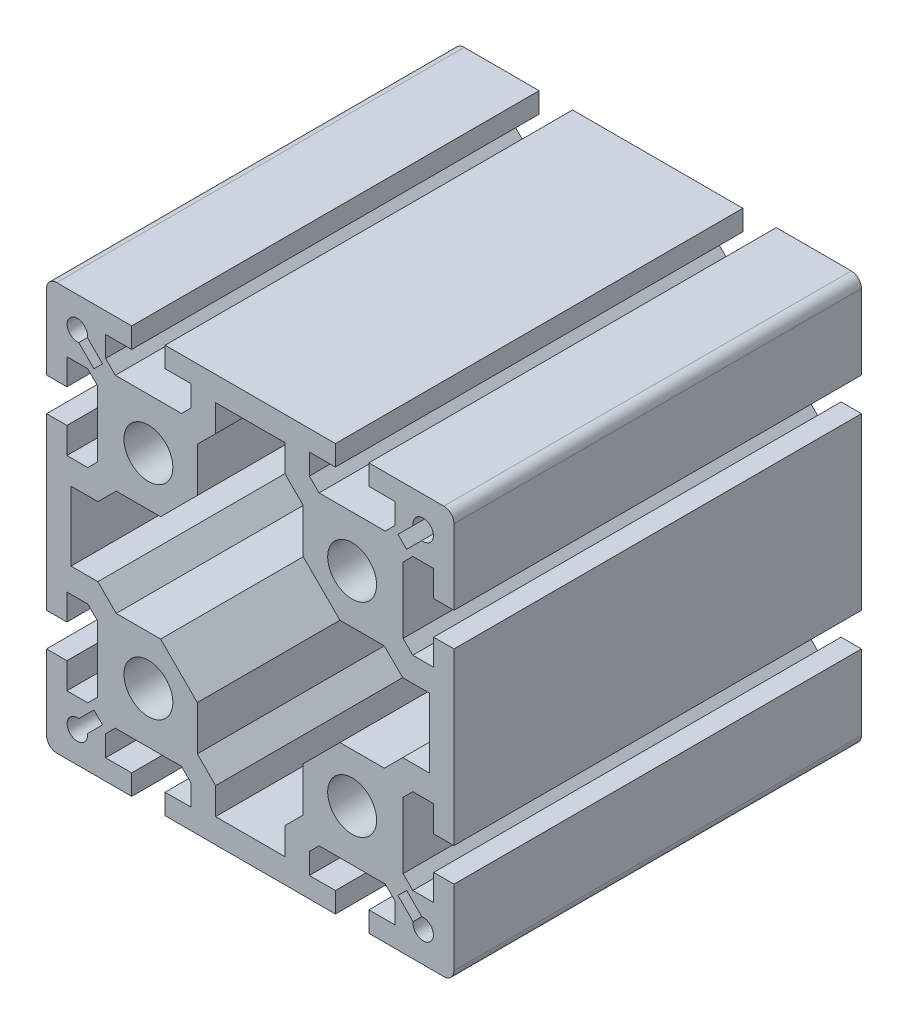
SolidWorks part; units mm, degrees
ref_plane "前视基准面" through (0, 0, 0) normal (0, 0, 1) x (1, 0, 0)
ref_plane "上视基准面" through (0, 0, 0) normal (0, 1, 0) x (1, 0, 0)
ref_plane "右视基准面" through (0, 0, 0) normal (1, 0, 0) x (0, 0, -1)
sketch "草图1" plane through (0, 0, 0) normal (0, 0, 1) x (1, 0, 0)
  line L0 (-28.6744, 51.3626) -> (-47.0744, 51.3626)
  line L1 (-49.5744, 48.8626) -> (-49.5744, 30.4626)
  line L2 (-24.5744, 38.8626) -> (-32.6903, 38.8626)
  line L3 (-37.0744, 34.4786) -> (-37.0744, 26.3626)
  line L4 (-28.6744, 46.3626) -> (-35.0744, 46.3626)
  line L5 (-44.5744, 36.8626) -> (-44.5744, 30.4626)
  line L6 (-35.0744, 46.3626) -> (-35.0744, 41.2467)
  line L7 (-28.6744, 51.3626) -> (-28.6744, 46.3626)
  line L8 (-39.4585, 36.8626) -> (-44.5744, 36.8626)
  line L9 (-44.5744, 30.4626) -> (-49.5744, 30.4626)
  line L10 (-32.6903, 38.8626) -> (-35.0744, 41.2467)
  line L11 (-37.0744, 34.4786) -> (-39.4585, 36.8626)
  line L12 (-35.8264, 39.7359) -> (-39.5416, 43.4511)
  line L13 (-37.9477, 37.6146) -> (-41.6629, 41.3298)
  line L14 (-37.9477, 37.6146) -> (-35.8264, 39.7359)
  line L15 (-24.5744, 38.8626) -> (-16.4585, 38.8626)
  line L16 (-20.4744, 46.3626) -> (-14.0744, 46.3626)
  line L17 (-14.0744, 46.3626) -> (-14.0744, 41.2467)
  line L18 (-8.0744, 45.3626) -> (-8.0744, 38.7614)
  line L19 (-20.4744, 51.3626) -> (-20.4744, 46.3626)
  line L20 (-16.4585, 38.8626) -> (-14.0744, 41.2467)
  line L21 (-12.5744, 34.2614) -> (-8.0744, 38.7614)
  line L22 (-20.4744, 51.3626) -> (0.4256, 51.3626)
  line L23 (-8.0744, 45.3626) -> (0.4256, 45.3626)
  line L24 (-37.0744, 26.3626) -> (-37.0744, 18.2467)
  line L25 (-44.5744, 22.2626) -> (-44.5744, 15.8626)
  line L26 (-44.5744, 15.8626) -> (-39.4585, 15.8626)
  line L27 (-37.0744, 18.2467) -> (-39.4585, 15.8626)
  line L28 (-49.5744, 22.2626) -> (-49.5744, 1.3626)
  line L29 (-44.5744, 22.2626) -> (-49.5744, 22.2626)
  line L30 (-12.5744, 23.3626) -> (-12.5744, 34.2614)
  line L31 (-43.5744, 9.8626) -> (-36.9732, 9.8626)
  line L32 (-32.4732, 14.3626) -> (-36.9732, 9.8626)
  line L33 (-43.5744, 9.8626) -> (-43.5744, 1.3626)
  line L34 (-21.5744, 14.3626) -> (-32.4732, 14.3626)
  line L35 (-12.5744, 23.3626) -> (-21.5744, 14.3626)
  line L36 (29.5256, 51.3626) -> (47.9256, 51.3626)
  line L37 (50.4256, 48.8626) -> (50.4256, 30.4626)
  line L38 (25.4256, 38.8626) -> (33.5415, 38.8626)
  line L39 (37.9256, 34.4786) -> (37.9256, 26.3626)
  line L40 (29.5256, 46.3626) -> (35.9256, 46.3626)
  line L41 (45.4256, 36.8626) -> (45.4256, 30.4626)
  line L42 (35.9256, 46.3626) -> (35.9256, 41.2467)
  line L43 (29.5256, 51.3626) -> (29.5256, 46.3626)
  line L44 (40.3097, 36.8626) -> (45.4256, 36.8626)
  line L45 (45.4256, 30.4626) -> (50.4256, 30.4626)
  line L46 (33.5415, 38.8626) -> (35.9256, 41.2467)
  line L47 (37.9256, 34.4786) -> (40.3097, 36.8626)
  line L48 (36.6776, 39.7359) -> (40.3928, 43.4511)
  line L49 (38.7989, 37.6146) -> (42.5141, 41.3298)
  line L50 (38.7989, 37.6146) -> (36.6776, 39.7359)
  line L51 (25.4256, 38.8626) -> (17.3097, 38.8626)
  line L52 (21.3256, 46.3626) -> (14.9256, 46.3626)
  line L53 (14.9256, 46.3626) -> (14.9256, 41.2467)
  line L54 (8.9256, 45.3626) -> (8.9256, 38.7614)
  line L55 (21.3256, 51.3626) -> (21.3256, 46.3626)
  line L56 (17.3097, 38.8626) -> (14.9256, 41.2467)
  line L57 (13.4256, 34.2614) -> (8.9256, 38.7614)
  line L58 (21.3256, 51.3626) -> (0.4256, 51.3626)
  line L59 (8.9256, 45.3626) -> (0.4256, 45.3626)
  line L60 (37.9256, 26.3626) -> (37.9256, 18.2467)
  line L61 (45.4256, 22.2626) -> (45.4256, 15.8626)
  line L62 (45.4256, 15.8626) -> (40.3097, 15.8626)
  line L63 (37.9256, 18.2467) -> (40.3097, 15.8626)
  line L64 (50.4256, 22.2626) -> (50.4256, 1.3626)
  line L65 (45.4256, 22.2626) -> (50.4256, 22.2626)
  line L66 (13.4256, 23.3626) -> (13.4256, 34.2614)
  line L67 (44.4256, 9.8626) -> (37.8244, 9.8626)
  line L68 (33.3244, 14.3626) -> (37.8244, 9.8626)
  line L69 (44.4256, 9.8626) -> (44.4256, 1.3626)
  line L70 (22.4256, 14.3626) -> (33.3244, 14.3626)
  line L71 (13.4256, 23.3626) -> (22.4256, 14.3626)
  line L72 (-28.6744, -48.6374) -> (-47.0744, -48.6374)
  line L73 (-49.5744, -46.1374) -> (-49.5744, -27.7374)
  line L74 (-24.5744, -36.1374) -> (-32.6903, -36.1374)
  line L75 (-37.0744, -31.7533) -> (-37.0744, -23.6374)
  line L76 (-28.6744, -43.6374) -> (-35.0744, -43.6374)
  line L77 (-44.5744, -34.1374) -> (-44.5744, -27.7374)
  line L78 (-35.0744, -43.6374) -> (-35.0744, -38.5214)
  line L79 (-28.6744, -48.6374) -> (-28.6744, -43.6374)
  line L80 (-39.4585, -34.1374) -> (-44.5744, -34.1374)
  line L81 (-44.5744, -27.7374) -> (-49.5744, -27.7374)
  line L82 (-32.6903, -36.1374) -> (-35.0744, -38.5214)
  line L83 (-37.0744, -31.7533) -> (-39.4585, -34.1374)
  line L84 (-35.8264, -37.0107) -> (-39.5416, -40.7259)
  line L85 (-37.9477, -34.8894) -> (-41.6629, -38.6045)
  line L86 (-37.9477, -34.8894) -> (-35.8264, -37.0107)
  line L87 (-24.5744, -36.1374) -> (-16.4585, -36.1374)
  line L88 (-20.4744, -43.6374) -> (-14.0744, -43.6374)
  line L89 (-14.0744, -43.6374) -> (-14.0744, -38.5214)
  line L90 (-8.0744, -42.6374) -> (-8.0744, -36.0362)
  line L91 (-20.4744, -48.6374) -> (-20.4744, -43.6374)
  line L92 (-16.4585, -36.1374) -> (-14.0744, -38.5214)
  line L93 (-12.5744, -31.5362) -> (-8.0744, -36.0362)
  line L94 (-20.4744, -48.6374) -> (0.4256, -48.6374)
  line L95 (-8.0744, -42.6374) -> (0.4256, -42.6374)
  line L96 (-37.0744, -23.6374) -> (-37.0744, -15.5214)
  line L97 (-44.5744, -19.5374) -> (-44.5744, -13.1374)
  line L98 (-44.5744, -13.1374) -> (-39.4585, -13.1374)
  line L99 (-37.0744, -15.5214) -> (-39.4585, -13.1374)
  line L100 (-49.5744, -19.5374) -> (-49.5744, 1.3626)
  line L101 (-44.5744, -19.5374) -> (-49.5744, -19.5374)
  line L102 (-12.5744, -20.6374) -> (-12.5744, -31.5362)
  line L103 (-43.5744, -7.1374) -> (-36.9732, -7.1374)
  line L104 (-32.4732, -11.6374) -> (-36.9732, -7.1374)
  line L105 (-43.5744, -7.1374) -> (-43.5744, 1.3626)
  line L106 (-21.5744, -11.6374) -> (-32.4732, -11.6374)
  line L107 (-12.5744, -20.6374) -> (-21.5744, -11.6374)
  line L108 (29.5256, -48.6374) -> (47.9256, -48.6374)
  line L109 (50.4256, -46.1374) -> (50.4256, -27.7374)
  line L110 (25.4256, -36.1374) -> (33.5415, -36.1374)
  line L111 (37.9256, -31.7533) -> (37.9256, -23.6374)
  line L112 (29.5256, -43.6374) -> (35.9256, -43.6374)
  line L113 (45.4256, -34.1374) -> (45.4256, -27.7374)
  line L114 (35.9256, -43.6374) -> (35.9256, -38.5214)
  line L115 (29.5256, -48.6374) -> (29.5256, -43.6374)
  line L116 (40.3097, -34.1374) -> (45.4256, -34.1374)
  line L117 (45.4256, -27.7374) -> (50.4256, -27.7374)
  line L118 (33.5415, -36.1374) -> (35.9256, -38.5214)
  line L119 (37.9256, -31.7533) -> (40.3097, -34.1374)
  line L120 (36.6776, -37.0107) -> (40.3928, -40.7259)
  line L121 (38.7989, -34.8894) -> (42.5141, -38.6045)
  line L122 (38.7989, -34.8894) -> (36.6776, -37.0107)
  line L123 (25.4256, -36.1374) -> (17.3097, -36.1374)
  line L124 (21.3256, -43.6374) -> (14.9256, -43.6374)
  line L125 (14.9256, -43.6374) -> (14.9256, -38.5214)
  line L126 (8.9256, -42.6374) -> (8.9256, -36.0362)
  line L127 (21.3256, -48.6374) -> (21.3256, -43.6374)
  line L128 (17.3097, -36.1374) -> (14.9256, -38.5214)
  line L129 (13.4256, -31.5362) -> (8.9256, -36.0362)
  line L130 (21.3256, -48.6374) -> (0.4256, -48.6374)
  line L131 (8.9256, -42.6374) -> (0.4256, -42.6374)
  line L132 (37.9256, -23.6374) -> (37.9256, -15.5214)
  line L133 (45.4256, -19.5374) -> (45.4256, -13.1374)
  line L134 (45.4256, -13.1374) -> (40.3097, -13.1374)
  line L135 (37.9256, -15.5214) -> (40.3097, -13.1374)
  line L136 (50.4256, -19.5374) -> (50.4256, 1.3626)
  line L137 (45.4256, -19.5374) -> (50.4256, -19.5374)
  line L138 (13.4256, -20.6374) -> (13.4256, -31.5362)
  line L139 (44.4256, -7.1374) -> (37.8244, -7.1374)
  line L140 (33.3244, -11.6374) -> (37.8244, -7.1374)
  line L141 (44.4256, -7.1374) -> (44.4256, 1.3626)
  line L142 (22.4256, -11.6374) -> (33.3244, -11.6374)
  line L143 (13.4256, -20.6374) -> (22.4256, -11.6374)
  arc A0 (-47.0744, 51.3626) -> (-49.5744, 48.8626) centre (-47.0744, 48.8626) ccw
  circle A1 centre (-24.5744, 26.3626) radius 6
  arc A2 (-39.5416, 43.4511) -> (-41.6629, 41.3298) centre (-42.0164, 43.8047) ccw
  arc A3 (50.4256, 48.8626) -> (47.9256, 51.3626) centre (47.9256, 48.8626) ccw
  circle A4 centre (25.4256, 26.3626) radius 6
  arc A5 (42.5141, 41.3298) -> (40.3928, 43.4511) centre (42.8676, 43.8047) ccw
  arc A6 (-49.5744, -46.1374) -> (-47.0744, -48.6374) centre (-47.0744, -46.1374) ccw
  circle A7 centre (-24.5744, -23.6374) radius 6
  arc A8 (-41.6629, -38.6045) -> (-39.5416, -40.7259) centre (-42.0164, -41.0794) ccw
  arc A9 (47.9256, -48.6374) -> (50.4256, -46.1374) centre (47.9256, -46.1374) ccw
  circle A10 centre (25.4256, -23.6374) radius 6
  arc A11 (40.3928, -40.7259) -> (42.5141, -38.6045) centre (42.8676, -41.0794) ccw
extrude "凸台-拉伸1" add sketch "草图1" along normal blind 100
